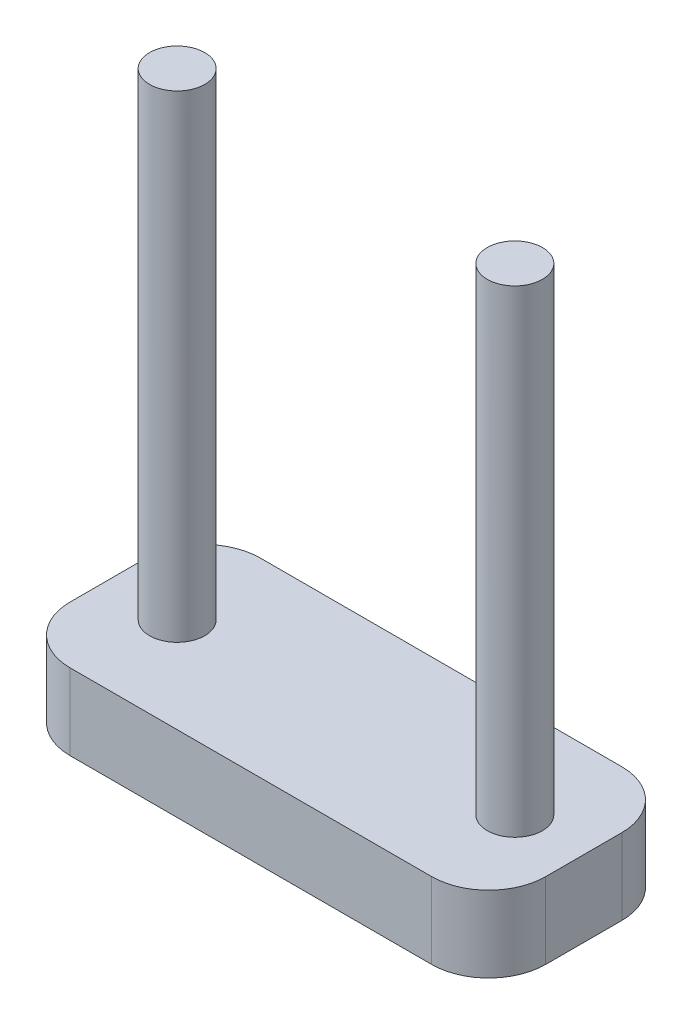
SolidWorks part; units mm, degrees
ref_plane "Front Plane" through (0, 0, 0) normal (0, 0, 1) x (1, 0, 0)
ref_plane "Top Plane" through (0, 0, 0) normal (0, 1, 0) x (1, 0, 0)
ref_plane "Right Plane" through (0, 0, 0) normal (1, 0, 0) x (0, 0, -1)
sketch "Sketch1" plane through (0, 0, 0) normal (0, 1, 0) x (1, 0, 0)
  line L1 (-12.5, -5) -> (12.5, -5)
  line L2 (-12.5, -5) -> (-12.5, 5)
  line L3 (-12.5, 5) -> (12.5, 5)
  line L4 (12.5, -5) -> (12.5, 5)
  line L5 (-12.5, -5) -> (12.5, 5) construction
  line L6 (-12.5, 5) -> (12.5, -5) construction
  point P0 (0, 0)
  dimension "D1" = 25
  dimension "D2" = 10
extrude "Boss-Extrude1" add sketch "Sketch1" along normal blind 4
sketch "Sketch2" plane through (0, 4, 0) normal (0, 1, 0) x (1, 0, 0)
  circle A0 centre (8.875, 0) radius 1.45
  circle A1 centre (-8.875, 0) radius 1.45
  dimension "D1" = 2.9
  dimension "D2" = 2.9
  dimension "D3" = 8.875
  dimension "D4" = 8.875
extrude "Boss-Extrude2" add sketch "Sketch2" along normal blind 25.1
fillet "Fillet1" radius 3 4 edges at (-12.5, 2, 5) (-12.5, 2, -5) (12.5, 2, -5) (12.5, 2, 5)
